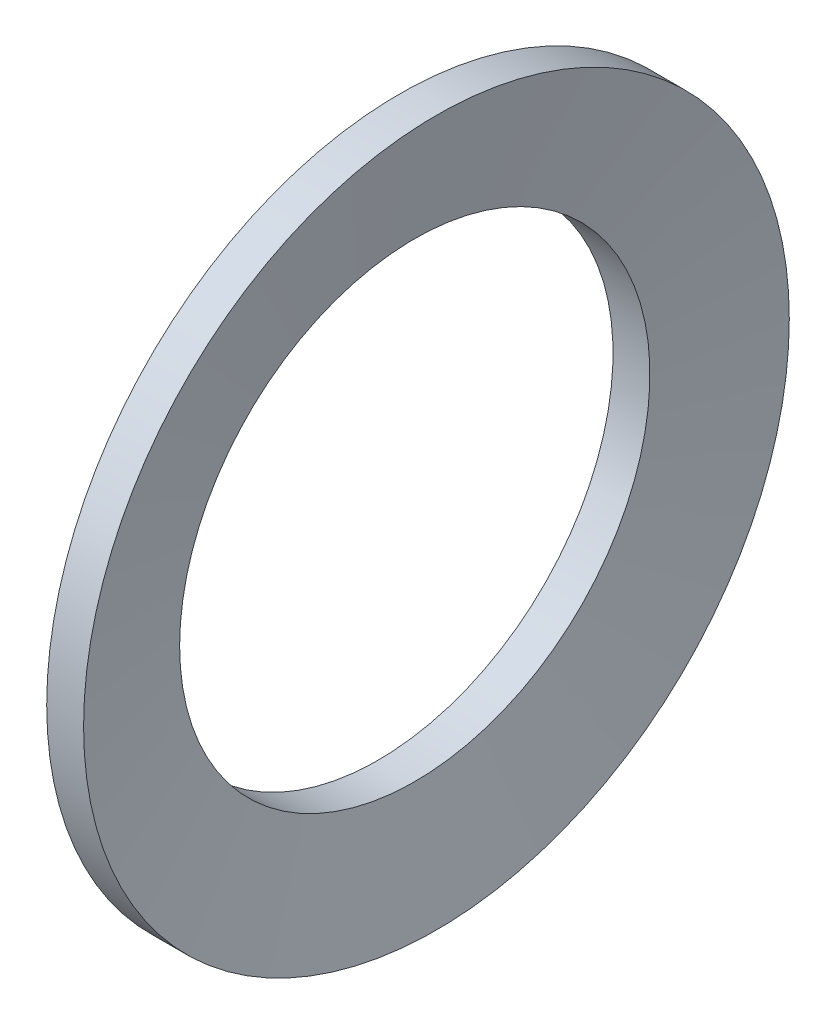
SolidWorks part; units mm, degrees
material "Plain Carbon Steel"
ref_plane "Front Plane" through (0, 0, 0) normal (0, 0, 1) x (1, 0, 0)
ref_plane "Top Plane" through (0, 0, 0) normal (0, 1, 0) x (1, 0, 0)
ref_plane "Right Plane" through (0, 0, 0) normal (1, 0, 0) x (0, 0, -1)
sketch "Sketch1" plane through (0, 0, 0) normal (0, 0, 1) x (1, 0, 0)
  line L0 (0, 0) -> (35.0997, 0) construction
  line L1 (-2.4892, 9.9949) -> (-1.5677, 14.9987)
  line L2 (-1.5677, 14.9987) -> (0, 14.9987)
  line L3 (0, 14.9987) -> (-0.9215, 9.9949)
  line L4 (-0.9215, 9.9949) -> (-2.4892, 9.9949)
  dimension "D1" = 9.9949
  dimension "D2" = 14.9987
  dimension "D3" = 2.4892
  dimension "D4" = 1.5418
revolve "Revolve1" add sketch "Sketch1" angle 360 about L0
